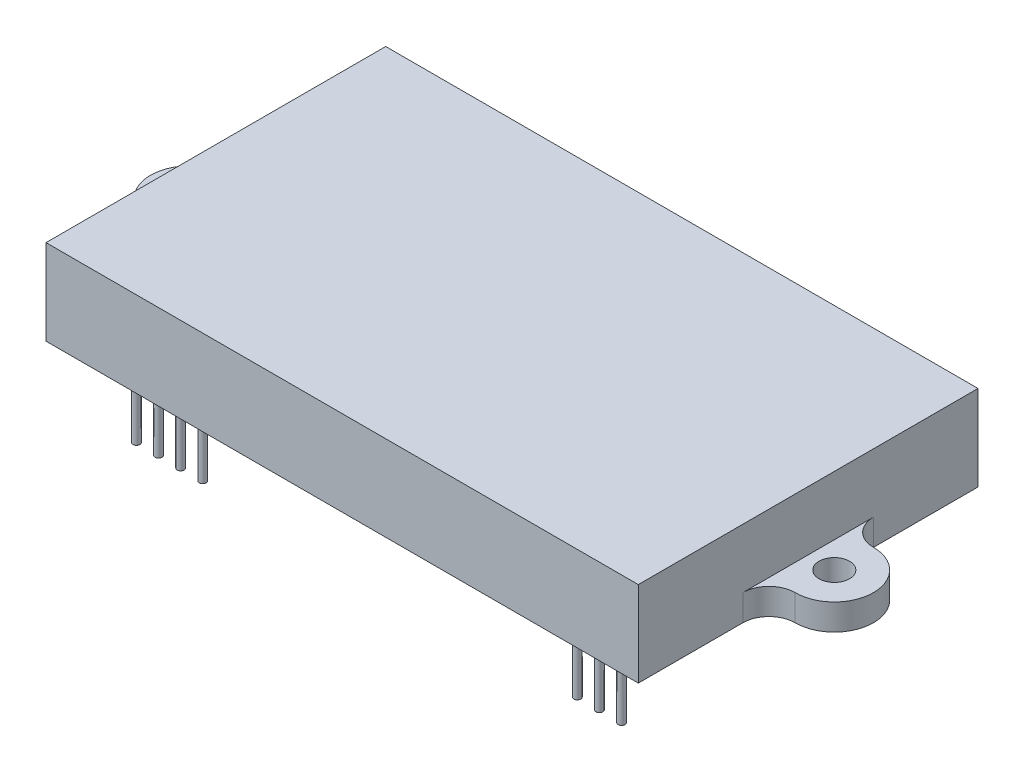
SolidWorks part; units mm, degrees
ref_plane "Plan de face" through (0, 0, 0) normal (0, 0, 1) x (1, 0, 0)
ref_plane "Plan de dessus" through (0, 0, 0) normal (0, 1, 0) x (1, 0, 0)
ref_plane "Plan de droite" through (0, 0, 0) normal (1, 0, 0) x (0, 0, -1)
sketch "Esquisse1" plane through (0, 0, 0) normal (0, 1, 0) x (1, 0, 0)
  line L1 (0, 0) -> (68, 0)
  line L2 (0, 0) -> (0, 39)
  line L3 (0, 39) -> (68, 39)
  line L4 (68, 0) -> (68, 39)
  point P34 (0, 0)
  point P40 (0, 0)
  point P41 (0, 0)
  point P42 (0, 0)
  point P43 (0, 0)
  point P44 (0, 0)
  dimension "D1" = 39
  dimension "D2" = 68
extrude "Boss.-Extru.3" add sketch "Esquisse1" along normal blind 9.8 contours L1 L4 L3 L2
sketch "Esquisse5" plane through (0, 0, 0) normal (0, 1, 0) x (1, 0, 0)
  line L0 (0, 0) -> (0, 39) construction
  line L1 (0, 0) -> (68, 0) construction
  line L3 (0, 27) -> (0, 12)
  circle A0 centre (-3, 19.5) radius 1.75
  arc A1 (-3, 24) -> (-3, 15) centre (-3, 19.5) ccw
  arc A2 (-3, 24) -> (0, 27) centre (-3, 27) ccw
  arc A3 (-3, 15) -> (0, 12) centre (-3, 12) cw
  dimension "D1" = 3
  dimension "D2" = 19.5
extrude "Boss.-Extru.5" add sketch "Esquisse5" along normal blind 3
sketch "Esquisse6" plane through (0, 0, 0) normal (0, 1, 0) x (1, 0, 0)
  line L0 (68, 0) -> (68, 39) construction
  line L1 (0, 0) -> (68, 0) construction
  line L2 (68, 12) -> (68, 27)
  circle A0 centre (71, 19.5) radius 1.75
  arc A1 (71, 24) -> (71, 15) centre (71, 19.5) cw
  arc A2 (71, 24) -> (68, 27) centre (71, 27) cw
  arc A3 (71, 15) -> (68, 12) centre (71, 12) ccw
  dimension "D1" = 3
  dimension "D2" = 19.5
extrude "Boss.-Extru.6" add sketch "Esquisse6" along normal blind 3
sketch "Esquisse7" plane through (0, 0, 0) normal (0, 1, 0) x (1, 0, 0)
  line L0 (0, 0) -> (68, 0) construction
  line L1 (14, 4) -> (11.46, 4) construction
  line L2 (57, 4) -> (59.54, 4) construction
  circle A0 centre (14, 4) radius 0.4
  circle A1 centre (11.46, 4) radius 0.4
  circle A2 centre (8.92, 4) radius 0.4
  circle A3 centre (6.38, 4) radius 0.4
  circle A4 centre (57, 4) radius 0.4
  circle A5 centre (59.54, 4) radius 0.4
  circle A6 centre (62.08, 4) radius 0.4
  point P4 (34, 0)
  point P15 (0, 0)
  dimension "D1" = 4
  dimension "D3" = 2.54
  dimension "D4" = 23
  dimension "D5" = 2.54
  dimension "D2" = 20
  dimension "D6" = 4
extrude "Boss.-Extru.7" add sketch "Esquisse7" against normal blind 8.9 contours A2
fillet "Congé1" radius 0.02 7 edges at (14, -8.9, -3.6) (62.08, -8.9, -3.6) (59.54, -8.9, -3.6) (57, -8.9, -3.6) (11.46, -8.9, -3.6) (8.92, -8.9, -3.6) (6.38, -8.9, -3.6)
